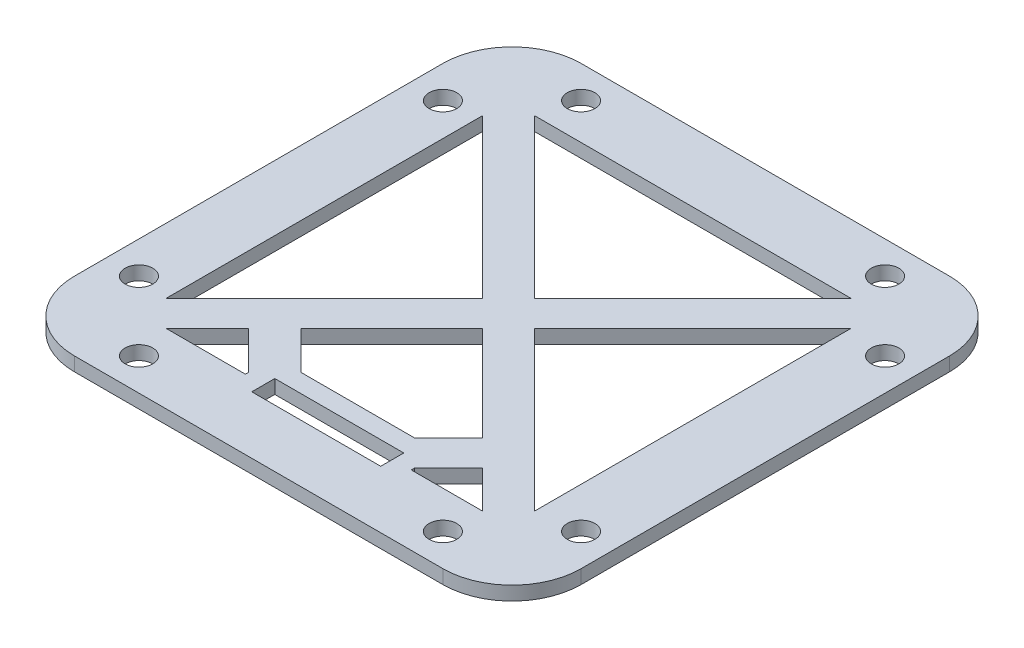
SolidWorks part; units mm, degrees
material "MDF"
ref_plane "Front Plane" through (0, 0, 0) normal (0, 0, 1) x (1, 0, 0)
ref_plane "Top Plane" through (0, 0, 0) normal (0, 1, 0) x (1, 0, 0)
ref_plane "Right Plane" through (0, 0, 0) normal (1, 0, 0) x (0, 0, -1)
sketch "Sketch1" plane through (0, 0, 0) normal (0, 1, 0) x (1, 0, 0)
  line L0 (55.8725, -40.1246) -> (55.8725, 39.8754)
  line L1 (40.8725, 54.8754) -> (-39.1275, 54.8754)
  line L2 (-54.1275, 39.8754) -> (-54.1275, -40.1246)
  line L3 (-39.1275, -55.1246) -> (40.8725, -55.1246)
  circle A0 centre (48.8725, 32.8754) radius 3
  circle A1 centre (-47.1275, -33.1246) radius 3
  circle A2 centre (-32.1275, -48.1246) radius 3
  circle A3 centre (33.8725, -48.1246) radius 3
  circle A4 centre (48.8725, -33.1246) radius 3
  circle A5 centre (33.8725, 47.8754) radius 3
  circle A6 centre (-32.1275, 47.8754) radius 3
  circle A7 centre (-47.1275, 32.8754) radius 3
  arc A8 (55.8725, 39.8754) -> (40.8725, 54.8754) centre (40.8725, 39.8754) ccw
  arc A9 (-39.1275, 54.8754) -> (-54.1275, 39.8754) centre (-39.1275, 39.8754) ccw
  arc A10 (-54.1275, -40.1246) -> (-39.1275, -55.1246) centre (-39.1275, -40.1246) ccw
  arc A11 (40.8725, -55.1246) -> (55.8725, -40.1246) centre (40.8725, -40.1246) ccw
extrude "Boss-Extrude1" add sketch "Sketch1" along normal blind 3
sketch "Sketch2" plane through (0, 3, 0) normal (0, 1, 0) x (1, 0, 0)
  line L0 (0.8725, -55.1246) -> (0.8725, -40.1246) construction
  line L1 (-39.1275, -55.1246) -> (40.8725, -55.1246) construction
  line L3 (-13.1275, -42.6246) -> (14.8725, -42.6246)
  line L4 (-13.1275, -42.6246) -> (-13.1275, -37.6246)
  line L5 (-13.1275, -37.6246) -> (14.8725, -37.6246)
  line L6 (14.8725, -42.6246) -> (14.8725, -37.6246)
  line L7 (-13.1275, -42.6246) -> (14.8725, -37.6246) construction
  line L8 (-13.1275, -37.6246) -> (14.8725, -42.6246) construction
  dimension "D1" = 15
  dimension "D2" = 28
  dimension "D3" = 5
extrude "Cut-Extrude1" cut sketch "Sketch2" against normal through all
sketch "Sketch3" plane through (0, 3, 0) normal (0, 1, 0) x (1, 0, 0)
  line L0 (40, -34.3431) -> (5.6569, 0)
  line L1 (34.3431, -40) -> (18.8725, -40)
  line L2 (40, -34.3431) -> (40, 34.3431)
  line L3 (34.3431, 40) -> (-34.3431, 40)
  line L4 (-40, -34.3431) -> (-40, 34.3431)
  line L5 (40, -40) -> (-40, 40) construction
  line L6 (40, 40) -> (-40, -40) construction
  line L7 (34.3431, 40) -> (0, 5.6569)
  line L8 (34.3431, -40) -> (26.2485, -31.9054)
  line L9 (40, 34.3431) -> (5.6569, 0)
  line L10 (42.8284, -37.1716) -> (-37.1716, 42.8284) construction
  line L11 (37.1716, -42.8284) -> (-42.8284, 37.1716) construction
  line L12 (37.1716, 42.8284) -> (-42.8284, -37.1716) construction
  line L13 (42.8284, 37.1716) -> (-37.1716, -42.8284) construction
  line L14 (0, 5.6569) -> (-34.3431, 40)
  line L15 (-5.6569, 0) -> (-40, -34.3431)
  line L16 (-5.6569, 0) -> (-40, 34.3431)
  line L17 (0, -5.6569) -> (-19.7192, -25.3761)
  line L18 (14.8725, -42.6246) -> (14.8725, -37.6246) construction
  line L19 (-13.1275, -37.6246) -> (-13.1275, -42.6246) construction
  line L20 (14.8725, -37.6246) -> (-13.1275, -37.6246) construction
  line L21 (14.8725, -42.6246) -> (14.8725, -37.6246) construction
  line L22 (-13.1275, -37.6246) -> (-13.1275, -42.6246) construction
  line L23 (14.8725, -37.6246) -> (-13.1275, -37.6246) construction
  line L24 (18.8725, -40) -> (18.8725, -39.2815)
  line L25 (13.2156, -33.6246) -> (-11.4707, -33.6246)
  line L26 (-17.1275, -39.2815) -> (-17.1275, -40)
  line L27 (-17.1275, -33.6246) -> (-17.1275, -42.6246) construction
  line L28 (18.8725, -42.6246) -> (18.8725, -33.6246) construction
  line L29 (-17.1275, -40) -> (-34.3431, -40)
  line L30 (-17.1275, -33.6246) -> (-22.5477, -28.2045) construction
  line L31 (18.8725, -33.6246) -> (23.4201, -29.077) construction
  line L32 (-11.4707, -33.6246) -> (-19.7192, -25.3761)
  line L33 (18.8725, -39.2815) -> (26.2485, -31.9054)
  line L34 (-17.1275, -39.2815) -> (-25.3761, -31.0329)
  line L35 (13.2156, -33.6246) -> (20.5917, -26.2485)
  line L36 (-14.2991, -30.7962) -> (-19.7192, -25.3761) construction
  line L37 (-19.956, -36.4531) -> (-25.3761, -31.0329) construction
  line L38 (16.044, -30.7962) -> (20.5917, -26.2485) construction
  line L39 (21.7009, -36.4531) -> (26.2485, -31.9054) construction
  line L40 (18.8725, -33.6246) -> (-17.1275, -33.6246) construction
  line L41 (-25.3761, -31.0329) -> (-34.3431, -40)
  line L42 (20.5917, -26.2485) -> (0, -5.6569)
  point P0 (0, 0)
  dimension "D1" = 80
  dimension "D2" = 80
  dimension "D3" = 4
  dimension "D4" = 4
  dimension "D5" = 4
  dimension "D6" = 4
  dimension "D7" = 4
extrude "Cut-Extrude2" cut sketch "Sketch3" against normal through all
